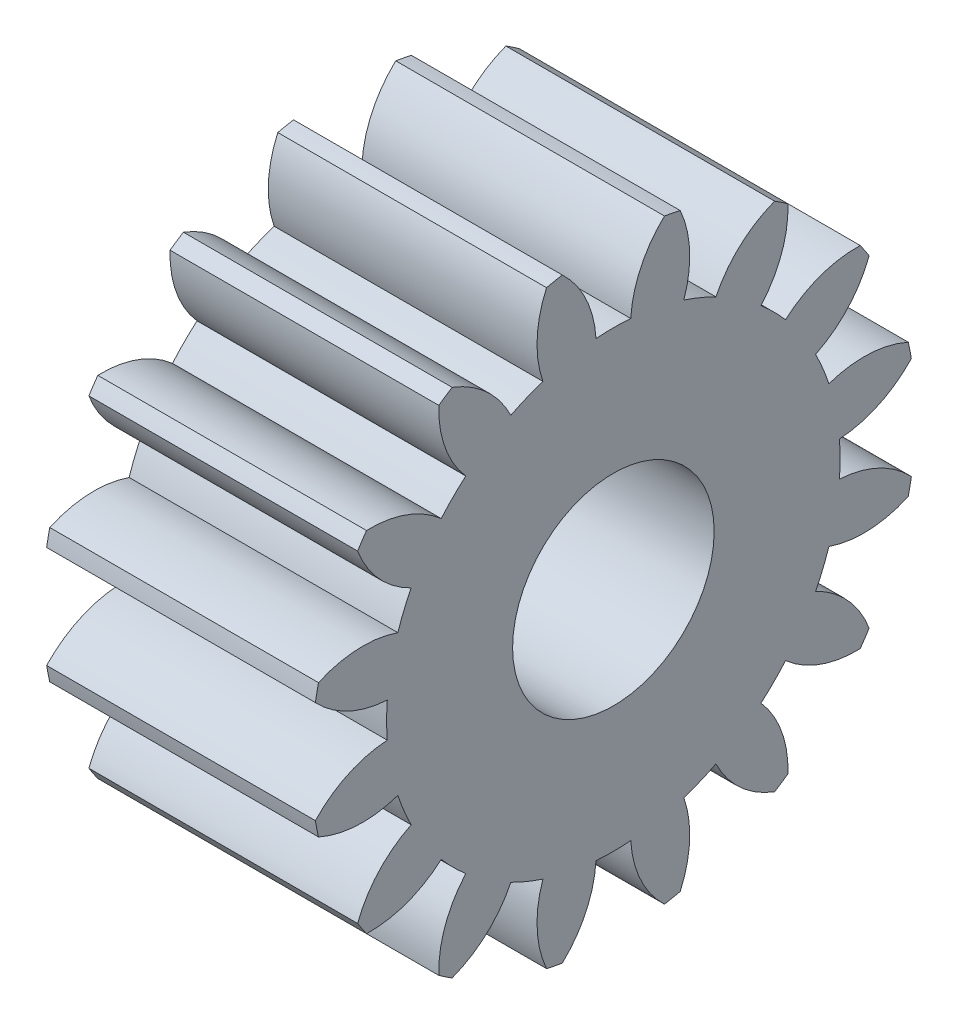
SolidWorks part; units mm, degrees
ref_plane "Plane1" through (0, 0, 0) normal (0, 0, 1) x (1, 0, 0)
ref_plane "Plane2" through (0, 0, 0) normal (0, 1, 0) x (1, 0, 0)
ref_plane "Plane3" through (0, 0, 0) normal (1, 0, 0) x (0, 0, -1)
sketch "HoldingSke" plane through (0, 0, 0) normal (0, 1, 0) x (1, 0, 0)
  line L0 (0, 0) -> (0.1923, -0.0551)
  line L1 (-15, 0) -> (100, 0) construction
  line L2 (0, 0) -> (-2.1039, 2.3779)
  line L3 (0, 0) -> (-11.863, 4.5341)
  line L4 (0, 0) -> (8.3015, 2.3804)
  line L5 (0, 0) -> (-46.8476, -17.4728)
  line L6 (0, 0) -> (-20.7241, -13.9826)
  line L7 (-2.1039, 2.3779) -> (8.6586, 51.2059)
  line L8 (-76.2, 54.61) -> (-72.9, 54.61)
  line L9 (-71.009, 38.7566) -> (-53.1078, 45.2721)
  line L10 (-76.2, 71.12) -> (104.1128, 71.12)
  line L11 (0, 0) -> (-25, 0)
  line L12 (-76.2, 101.6) -> (-76.033, 101.6)
  line L13 (24.9733, 27.94) -> (52.9518, 28.4284)
  line L14 (24.9733, 27.94) -> (24.9743, 27.94)
  line L15 (24.9733, 27.94) -> (100.4006, 29.5858)
  line L16 (-63.627, -5) -> (-12.827, -5)
  circle A0 centre (0, 0) radius 15
  circle A1 centre (0, 0) radius 33.749
  circle A2 centre (0, 0) radius 37.5
  circle A3 centre (0, 0) radius 15
  dimension "MHD" = 67.498
  dimension "Hub_dia" = 75
  dimension "Bore" = 30
  dimension "MBD" = 30
  dimension "Num_teeth" = 16
  dimension "Pitch" = 0.2
  dimension "Overall_len" = 50
  dimension "Show_teeth" = 16
  dimension "Thickness" = 25
  dimension "OAL" = 50.0001
  dimension "T_dim" = 3.3
  dimension "Ap" = 20
  dimension "H" = 19.05
  dimension "Pitch_radius" = 180.3128
  dimension "Width" = 25
  dimension "Backlash" = 0.167
  dimension "Addendum_fac" = 1
  dimension "Dedendum_fac" = 1.25
  dimension "Clearance_fac" = 0.25
  dimension "Dedendum_add" = 0.001
  dimension "Module" = 5
sketch "BasProSke" plane through (0, 0, 0) normal (0, 1, 0) x (1, 0, 0)
  line L0 (-10, 0) -> (60, 0) construction
  line L1 (0, 0) -> (0, 45)
  line L2 (0, 0) -> (40, 0)
  line L3 (40, 0) -> (40, 45)
  line L4 (40, 45) -> (0, 45)
  dimension "Thickness" = 40
  dimension "Diameter" = 90
revolve "Base-Revolve" add sketch "BasProSke" angle 360 about L0
sketch "TooCutSke" plane through (0, 0, 0) normal (1, 0, 0) x (0, 0, -1)
  line L1 (0, 0) -> (0, 107) construction
  line L2 (0, 0) -> (-4.2127, 39.7775) construction
  line L3 (0, 0) -> (-15.5429, 78.1393) construction
  line L4 (-4.2127, 39.7775) -> (-7.7714, 39.0697) construction
  arc A0 (2.5852, 33.6498) -> (-2.5852, 33.6498) centre (0, 0) ccw
  arc A1 (7.6282, 44.3745) -> (-7.6282, 44.3745) centre (0, 0) ccw
  circle A2 centre (0, 0) radius 40 construction
  circle A3 centre (0, 0) radius 37.5877 construction
  arc A4 (-2.5852, 33.6498) -> (-7.6282, 44.3745) centre (-18.5563, 32.6879) ccw
  arc A5 (7.6282, 44.3745) -> (2.5852, 33.6498) centre (18.5563, 32.6879) ccw
  dimension "Root_dia" = 67.498
  dimension "Overcut_dia" = 90.0508
  dimension "Pitch_dia" = 80
  dimension "Base_dia" = 75.1754
  dimension "Flank_rad" = 16
  dimension "Half_ang" = 11.25
  dimension "Half_CT" = 3.6284
extrude "ToothCut" cut sketch "TooCutSke" along normal through all
fillet "Breaks" [suppressed] radius 0.1
fillet "RootFillets" [suppressed] radius 1.251
pattern_circular "TeethCuts" count 16 every 22.5 about axis through (-10, 0, 0) along (1, 0, 0) of "ToothCut", "RootFillets", "Breaks"
sketch "HubNeaOneSke" plane through (0, 0, 0) normal (-1, 0, 0) x (0, 0, 1)
  circle A0 centre (0, 0) radius 33.749
  dimension "Diameter" = 67.498
extrude "HubNearOne" [suppressed] add sketch "HubNeaOneSke" along normal blind 10.0001
sketch "HubNeaBotSke" plane through (0, 0, 0) normal (-1, 0, 0) x (0, 0, 1)
  circle A0 centre (0, 0) radius 33.749
  dimension "Diameter" = 67.498
extrude "HubNearBoth" [suppressed] add sketch "HubNeaBotSke" along normal blind 5
ref_plane "FarPln" through (40, 0, 0) normal (1, 0, 0) x (0, 0, -1)
sketch "HubFarSke" plane through (40, 0, 0) normal (1, 0, 0) x (0, 0, -1)
  circle A0 centre (0, 0) radius 33.749
  dimension "Diameter" = 67.498
extrude "HubFar" [suppressed] add sketch "HubFarSke" along normal blind 5
sketch "BorSke" plane through (0, 0, 0) normal (1, 0, 0) x (0, 0, -1)
  circle A0 centre (0, 0) radius 15
  dimension "Diameter" = 30
extrude "Bore" cut sketch "BorSke" along normal mid plane 100.0001
sketch "KeySke" plane through (0, 0, 0) normal (1, 0, 0) x (0, 0, -1)
  line L0 (-4, 0) -> (-4, 18.3)
  line L1 (-4, 18.3) -> (4, 18.3)
  line L2 (4, 18.3) -> (4, 0)
  line L3 (0, 0) -> (0, 34) construction
  line L4 (-4, 0) -> (4, 0)
  dimension "Offset" = 18.3
  dimension "Width" = 8
extrude "Keyway" [suppressed] cut sketch "KeySke" along normal mid plane 100.0001
pattern_circular "Keyway2" [suppressed] count 2 every 90 about axis through (-10, 0, 0) along (1, 0, 0)
equation "' \"Module@HoldingSke\" = 6.35"
equation "' \"Num_teeth@HoldingSke\" = 12"
equation "' \"Ap@HoldingSke\" =  20"
equation "' \"Ap@HoldingSke\" = 20"
equation "' \"Width@HoldingSke\" = 0.5 * 25.4"
equation "' \"Hub_dia@HoldingSke\"= 1 * 25.4"
equation "' \"Hub_dia@HoldingSke\" = 1 * 25.4"
equation "' \"Overall_len@HoldingSke\" = 1.0 * 25.4"
equation "' \"Bore@HoldingSke\" = 0.75 * 25.4"
equation "' \"T_dim@HoldingSke\" = 0.1 * 25.4"
equation "' \"Width@KeySke\" = 0.25 * 25.4"
equation "' \"Show_teeth@HoldingSke\" = 13"
equation "' \"Backlash@HoldingSke\" = 0.009 * 25.4"
equation "' \"Addendum_fac@HoldingSke\" = 1.0"
equation "' \"Dedendum_fac@HoldingSke\" = 1.25"
equation "' \"Dedendum_add@HoldingSke\" = 0.00005 * 25.4"
equation "' \"Clearance_fac@HoldingSke\" = 0.25"
equation "\"Pitch@HoldingSke\" = 1 / \"Module@HoldingSke\""
equation "\"Overcut_dia@TooCutSke\" = (\"Num_teeth@HoldingSke\" + 2 * \"Addendum_fac@HoldingSke\") / \"Pitch@HoldingSke\" + 0.002 * 25.4"
equation "\"Pitch_dia@TooCutSke\" = \"Num_teeth@HoldingSke\" / \"Pitch@HoldingSke\""
equation "\"Base_dia@TooCutSke\" = \"Num_teeth@HoldingSke\" / \"Pitch@HoldingSke\" * cos((\"Ap@HoldingSke\"  * 3.14159265 / 180))"
equation "\"Root_dia@TooCutSke\" = (\"Num_teeth@HoldingSke\" + 2) / \"Pitch@HoldingSke\" - 2 * (\"Addendum_fac@HoldingSke\" + \"Dedendum_fac@HoldingSke\") / \"Pitch@HoldingSke\" - \"Dedendum_add@HoldingSke\" * 2"
equation "\"Half_ang@TooCutSke\" = 180 / \"Num_teeth@HoldingSke\""
equation "\"Half_CT@TooCutSke\" = \"Num_teeth@HoldingSke\" / \"Pitch@HoldingSke\" * sin((3.14159265 / 2 / \"Num_teeth@HoldingSke\")) / 2 - 7 * \"Backlash@HoldingSke\" / 4"
equation "\"Flank_rad@TooCutSke\" = \"Num_teeth@HoldingSke\" / \"Pitch@HoldingSke\" / 5"
equation "\"Radius@RootFillets\" = \"Clearance_fac@HoldingSke\" / \"Pitch@HoldingSke\" + \"Dedendum_add@HoldingSke\""
equation "\"Break_rad@Breaks\" = 0.02 / \"Pitch@HoldingSke\""
equation "\"Thickness@HoldingSke\" = \"Width@HoldingSke\""
equation "\"OAL@HoldingSke\" = \"Thickness@HoldingSke\""
equation "\"MHD@HoldingSke\" = (\"Num_teeth@HoldingSke\" + 2) / \"Pitch@HoldingSke\" - 2 * (\"Addendum_fac@HoldingSke\" + \"Dedendum_fac@HoldingSke\")  / \"Pitch@HoldingSke\" - \"Dedendum_add@HoldingSke\" * 2"
equation "\"MBD@HoldingSke\" = (\"Num_teeth@HoldingSke\" + 2) / \"Pitch@HoldingSke\" - 2 * (\"Addendum_fac@HoldingSke\" + \"Dedendum_fac@HoldingSke\")  / \"Pitch@HoldingSke\" - \"Dedendum_add@HoldingSke\" * 2 - 0.002 * 25.4"
equation "\"MHD@HoldingSke\" = ((sgn( \"MHD@HoldingSke\" - \"Hub_dia@HoldingSke\" )-1)*( \"MHD@HoldingSke\" - \"Hub_dia@HoldingSke\" ))/-2+ \"Hub_dia@HoldingSke\""
equation "\"MBD@HoldingSke\" = ((sgn( \"MBD@HoldingSke\" - \"Bore@HoldingSke\" )-1)*( \"MBD@HoldingSke\" - \"Bore@HoldingSke\" ))/-2+ \"Bore@HoldingSke\""
equation "\"OAL@HoldingSke\" = ((sgn( \"OAL@HoldingSke\" - \"Overall_len@HoldingSke\" )+1)*( \"OAL@HoldingSke\" - \"Overall_len@HoldingSke\" ))/2 + \"Overall_len@HoldingSke\" + 0.000002 * 25.4"
equation "\"Num_teeth@TeethCuts\" = int( \"Show_teeth@HoldingSke\" ) + 1"
equation "\"Num_teeth@TeethCuts\" = ((sgn( \"Num_teeth@TeethCuts\" - \"Num_teeth@HoldingSke\" )-1)*( \"Num_teeth@TeethCuts\" - \"Num_teeth@HoldingSke\" ))/-2+ \"Num_teeth@HoldingSke\""
equation "\"Num_teeth@TeethCuts\" = ((sgn( \"Num_teeth@TeethCuts\" - 2.0)+1)*( \"Num_teeth@TeethCuts\" - 2.0))/2 +2.0"
equation "\"Angle@TeethCuts\" = 360.0 / \"Num_teeth@HoldingSke\""
equation "\"Diameter@BasProSke\" = (\"Num_teeth@HoldingSke\" + 2 * \"Addendum_fac@HoldingSke\") / \"Pitch@HoldingSke\""
equation "\"Thickness@BasProSke\"=\"Thickness@HoldingSke\"+15"
equation "' \"Fillet_rad@BasProSke\" =  \"Thickness@HoldingSke\" * 0.05"
equation "' \"Fillet_rad@BasProSke\" = \"Thickness@HoldingSke\" * 0.05"
equation "\"MHD@HoldingSke\" = ((sgn( \"MHD@HoldingSke\" - \"Root_dia@TooCutSke\" )-1)*( \"MHD@HoldingSke\" - \"Root_dia@TooCutSke\" ))/-2+ \"Root_dia@TooCutSke\""
equation "\"Diameter@HubNeaOneSke\" = \"MHD@HoldingSke\""
equation "\"Length@HubNearOne\" = \"OAL@HoldingSke\" - \"Thickness@BasProSke\""
equation "\"Diameter@HubNeaBotSke\" = \"MHD@HoldingSke\""
equation "\"Length@HubNearBoth\" = ( \"OAL@HoldingSke\" - \"Thickness@BasProSke\" ) / 2.0"
equation "\"Thickness@FarPln\" = \"Thickness@BasProSke\""
equation "\"Diameter@HubFarSke\" = \"MHD@HoldingSke\""
equation "\"Length@HubFar\" = ( \"OAL@HoldingSke\" - \"Thickness@BasProSke\" ) / 2.0"
equation "\"Diameter@BorSke\" = \"MBD@HoldingSke\""
equation "\"D1@Bore\" = \"OAL@HoldingSke\" * 2.0"
equation "\"D1@Keyway\" = \"OAL@HoldingSke\" * 2.0"
equation "\"Offset@KeySke\" = \"T_dim@HoldingSke\" + \"MBD@HoldingSke\" / 2.0"
